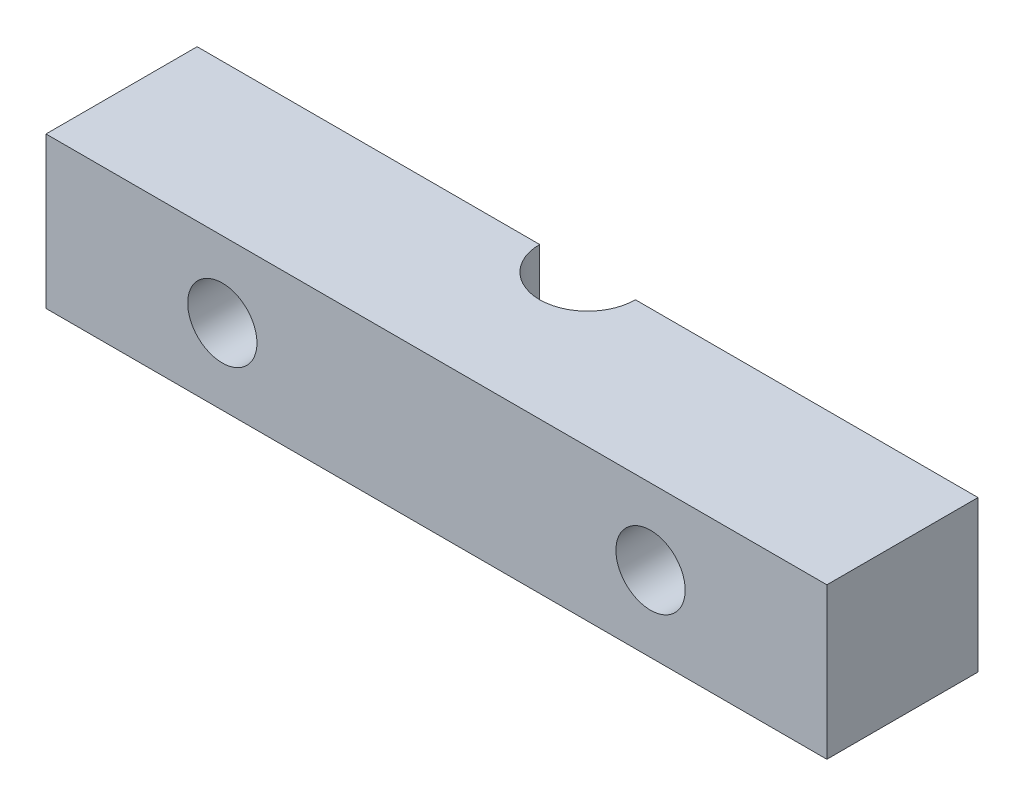
SolidWorks part; units mm, degrees
ref_plane "Front Plane" through (0, 0, 0) normal (0, 0, 1) x (1, 0, 0)
ref_plane "Top Plane" through (0, 0, 0) normal (0, 1, 0) x (1, 0, 0)
ref_plane "Right Plane" through (0, 0, 0) normal (1, 0, 0) x (0, 0, -1)
sketch "Sketch1" plane through (0, 0, 0) normal (0, 0, 1) x (1, 0, 0)
  line L0 (-15.5, 0) -> (15.5, 0) construction
  line L1 (-15.5, 3) -> (15.5, 3)
  line L2 (-15.5, 3) -> (-15.5, -3)
  line L3 (-15.5, -3) -> (15.5, -3)
  line L4 (15.5, 3) -> (15.5, -3)
  line L5 (-15.5, 3) -> (15.5, -3) construction
  line L6 (-15.5, -3) -> (15.5, 3) construction
  circle A0 centre (-8.5, 0) radius 1.375
  circle A1 centre (8.5, 0) radius 1.375
  point P0 (0, 0)
  point P12 (0, 0)
  point P13 (0, 0)
  dimension "D3" = 2.75
  dimension "D4" = 17
  dimension "D5" = 7
  dimension "D1" = 6
  dimension "D2" = 31
extrude "Base" add sketch "Sketch1" along normal blind 6
sketch "Sketch2" plane through (0, 3, 0) normal (0, 1, 0) x (1, 0, 0)
  line L0 (15.5, 0) -> (-15.5, 0) construction
  line L1 (-1.9, 0) -> (1.9, 0)
  arc A0 (-1.9, 0) -> (1.9, 0) centre (0, 0) ccw
  dimension "D1" = 1.9
extrude "Wire Grove" cut sketch "Sketch2" against normal through all
